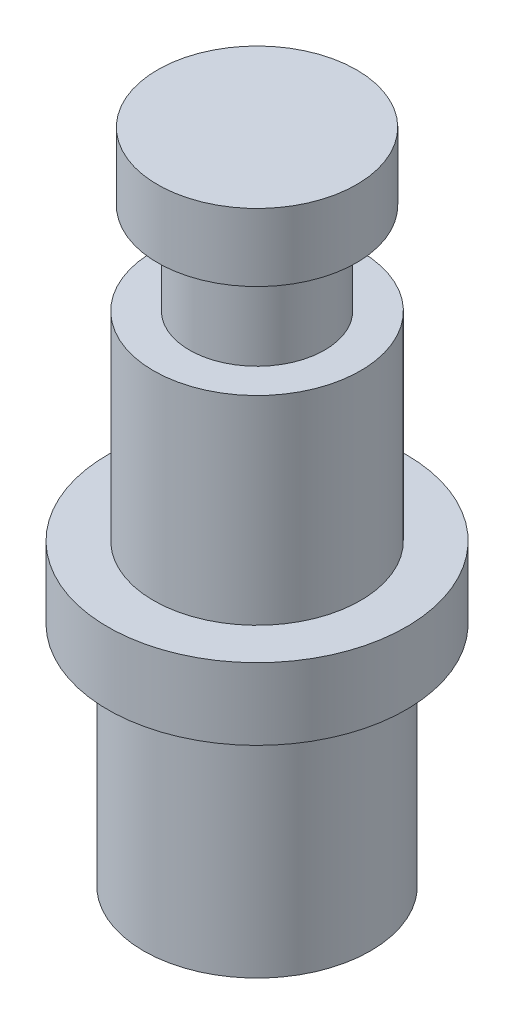
SolidWorks part; units mm, degrees
ref_plane "Front Plane" through (0, 0, 0) normal (0, 0, 1) x (1, 0, 0)
ref_plane "Top Plane" through (0, 0, 0) normal (0, 1, 0) x (1, 0, 0)
ref_plane "Right Plane" through (0, 0, 0) normal (1, 0, 0) x (0, 0, -1)
sketch "Sketch1" plane through (0, 0, 0) normal (0, 0, 1) x (1, 0, 0)
  line L0 (0, 0) -> (0, 72.3958) construction
sketch "Sketch2" plane through (0, 0, 0) normal (0, 0, 1) x (1, 0, 0)
  line L0 (0, 0) -> (3.6195, 0)
  line L1 (3.6195, 0) -> (3.6195, 7.239)
  line L2 (3.6195, 7.239) -> (4.7625, 7.239)
  line L3 (4.7625, 7.239) -> (4.7625, 9.525)
  line L4 (4.7625, 9.525) -> (3.302, 9.525)
  line L5 (3.302, 9.525) -> (3.302, 15.875)
  line L6 (3.302, 15.875) -> (2.159, 15.875)
  line L7 (2.159, 15.875) -> (2.159, 18.796)
  line L8 (2.159, 18.796) -> (3.175, 18.796)
  line L9 (3.175, 18.796) -> (3.175, 20.955)
  line L10 (3.175, 20.955) -> (0, 20.955)
  line L11 (0, 20.955) -> (0, 0)
  dimension "D1" = 20.955
  dimension "D2" = 3.6195
  dimension "D3" = 4.7625
  dimension "D4" = 3.302
  dimension "D5" = 2.159
  dimension "D6" = 3.175
  dimension "D7" = 7.239
  dimension "D8" = 2.286
  dimension "D9" = 6.35
  dimension "D10" = 2.921
revolve "Revolve1" add sketch "Sketch2" angle 360 about L0
